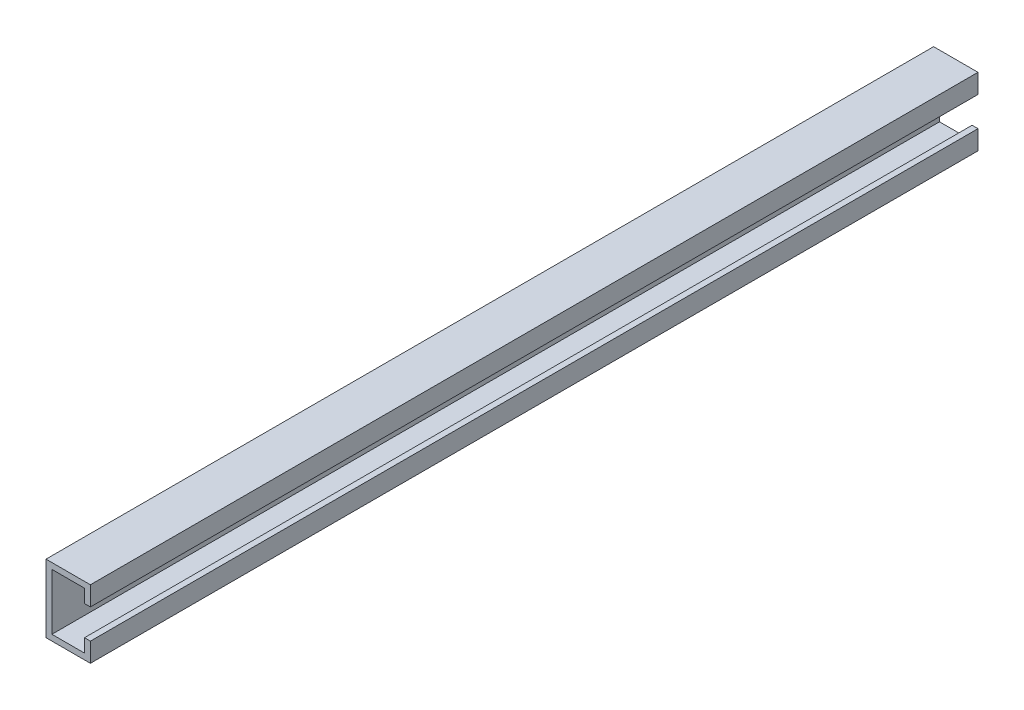
SolidWorks part; units mm, degrees
ref_plane "前视基准面" through (0, 0, 0) normal (0, 0, 1) x (1, 0, 0)
ref_plane "上视基准面" through (0, 0, 0) normal (0, 1, 0) x (1, 0, 0)
ref_plane "右视基准面" through (0, 0, 0) normal (1, 0, 0) x (0, 0, -1)
sketch "草图1" plane through (0, 0, 0) normal (0, 0, 1) x (1, 0, 0)
  line L0 (0, 0) -> (15, 0)
  line L1 (15, 0) -> (15, -6.5)
  line L2 (15, -6.5) -> (13, -6.5)
  line L3 (13, -6.5) -> (13, -2)
  line L4 (13, -2) -> (2, -2)
  line L5 (2, -2) -> (2, -21)
  line L6 (2, -21) -> (13, -21)
  line L7 (13, -21) -> (13, -16.5)
  line L8 (13, -16.5) -> (15, -16.5)
  line L9 (15, -16.5) -> (15, -23)
  line L10 (15, -23) -> (0, -23)
  line L11 (0, -23) -> (0, 0)
  line L12 (13, -6.5) -> (13, -16.5) construction
  line L13 (13, -11.5) -> (2, -11.5) construction
  line L14 (0, -11.5) -> (2, -11.5) construction
  point P16 (0, 0)
  dimension "D1" = 23
  dimension "D2" = 15
  dimension "D3" = 2
  dimension "D4" = 2
  dimension "D5" = 2
  dimension "D6" = 10
extrude "凸台-拉伸1" add sketch "草图1" along normal blind 300
